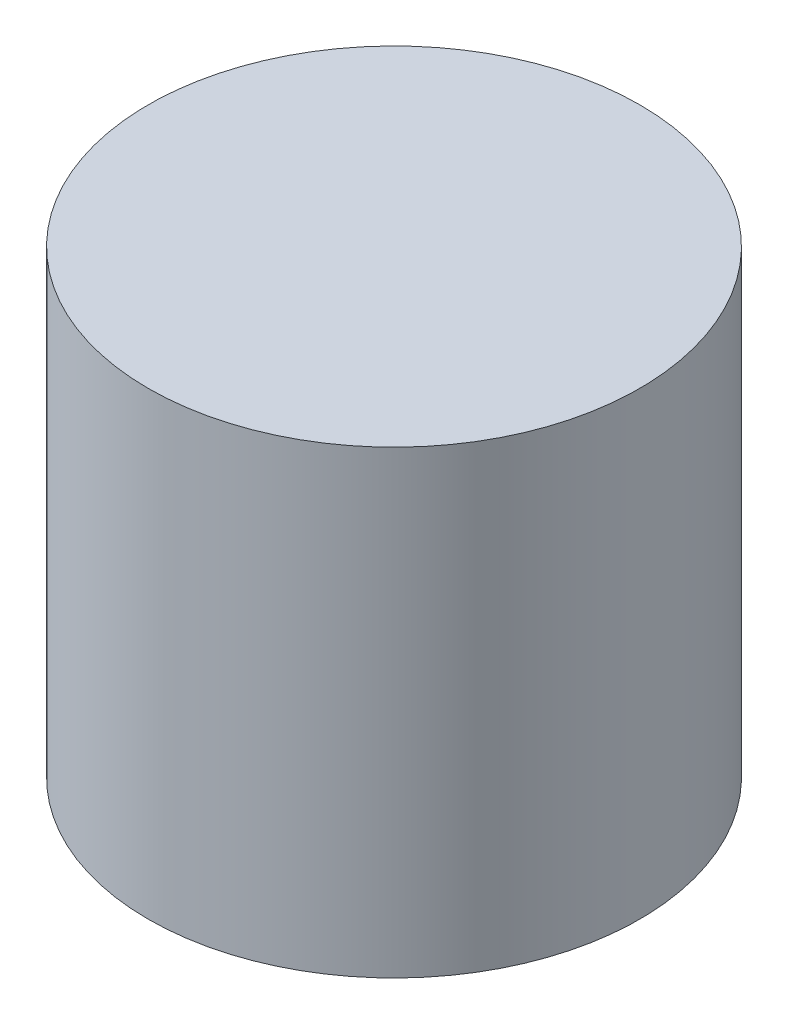
SolidWorks part; units mm, degrees
ref_plane "前视基准面" through (0, 0, 0) normal (0, 0, 1) x (1, 0, 0)
ref_plane "上视基准面" through (0, 0, 0) normal (0, 1, 0) x (1, 0, 0)
ref_plane "右视基准面" through (0, 0, 0) normal (1, 0, 0) x (0, 0, -1)
sketch "草图1" plane through (0, 0, 0) normal (0, 1, 0) x (1, 0, 0)
  circle A0 centre (0, 0) radius 3.1
  dimension "D1" = 6.2
extrude "凸台-拉伸1" add sketch "草图1" along normal blind 5.8
sketch "草图2" plane through (0, 0, 0) normal (0, -1, 0) x (1, 0, 0)
  circle A0 centre (0, 0) radius 1.5
  dimension "D1" = 3
extrude "切除-拉伸1" cut sketch "草图2" against normal blind 4.8
